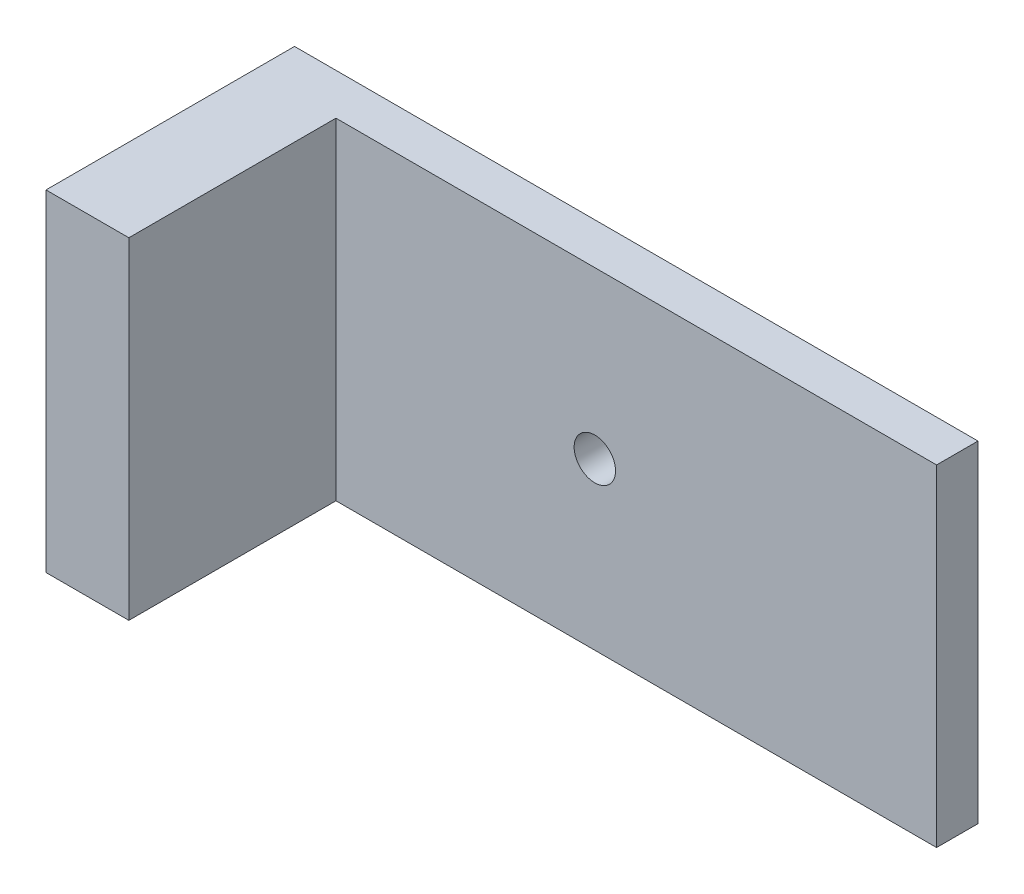
SolidWorks part; units mm, degrees
ref_plane "Front Plane" through (0, 0, 0) normal (0, 0, 1) x (1, 0, 0)
ref_plane "Top Plane" through (0, 0, 0) normal (0, 1, 0) x (1, 0, 0)
ref_plane "Right Plane" through (0, 0, 0) normal (1, 0, 0) x (0, 0, -1)
sketch "Sketch1" plane through (0, 0, 0) normal (0, 0, 1) x (1, 0, 0)
  line L1 (-82.5, -40) -> (82.5, -40)
  line L2 (-82.5, -40) -> (-82.5, 40)
  line L3 (-82.5, 40) -> (82.5, 40)
  line L4 (82.5, -40) -> (82.5, 40)
  line L5 (-82.5, -40) -> (82.5, 40) construction
  line L6 (-82.5, 40) -> (82.5, -40) construction
  point P0 (0, 0)
  dimension "D1" = 165
  dimension "D2" = 80
extrude "Boss-Extrude1" add sketch "Sketch1" along normal blind 10
sketch "Sketch2" plane through (0, 0, 10) normal (0, 0, 1) x (1, 0, 0)
  line L0 (-82.5, -40) -> (82.5, -40) construction
  line L1 (-82.5, 40) -> (-62.5, 40)
  line L2 (-82.5, 40) -> (-82.5, -40)
  line L3 (-82.5, -40) -> (-62.5, -40)
  line L12 (-62.5, 40) -> (-62.5, -40)
  dimension "D1" = 20
extrude "Boss-Extrude2" add sketch "Sketch2" along normal blind 50
sketch "Sketch3" plane through (0, 0, 10) normal (0, 0, 1) x (1, 0, 0)
  circle A0 centre (0, 0) radius 5
  dimension "D1" = 10
extrude "Cut-Extrude1" cut sketch "Sketch3" against normal up to next
